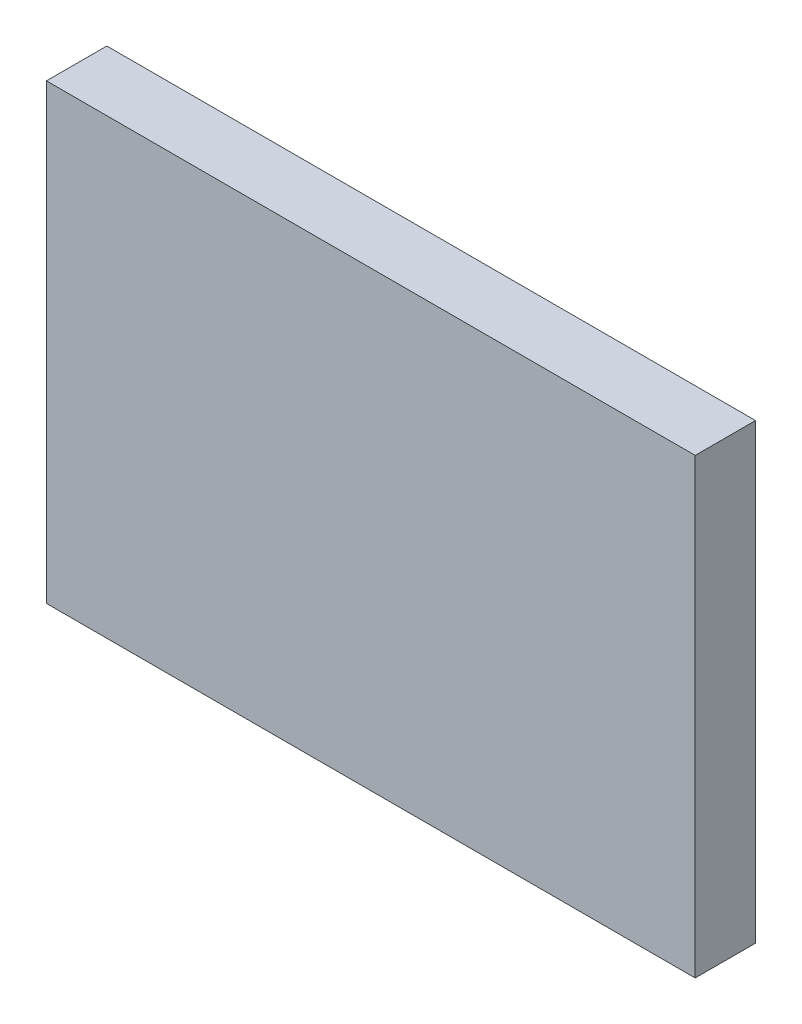
SolidWorks part; units mm, degrees
ref_plane "Alzado" through (0, 0, 0) normal (0, 0, 1) x (1, 0, 0)
ref_plane "Planta" through (0, 0, 0) normal (0, 1, 0) x (1, 0, 0)
ref_plane "Vista lateral" through (0, 0, 0) normal (1, 0, 0) x (0, 0, -1)
sketch "Croquis1" plane through (0, 0, 0) normal (0, 0, 1) x (1, 0, 0)
  line L1 (0, 0) -> (43, 0)
  line L2 (0, 0) -> (0, -30)
  line L3 (0, -30) -> (43, -30)
  line L4 (43, 0) -> (43, -30)
  dimension "D1" = 43
  dimension "D2" = 30
extrude "Saliente-Extruir1" add sketch "Croquis1" along normal blind 4
